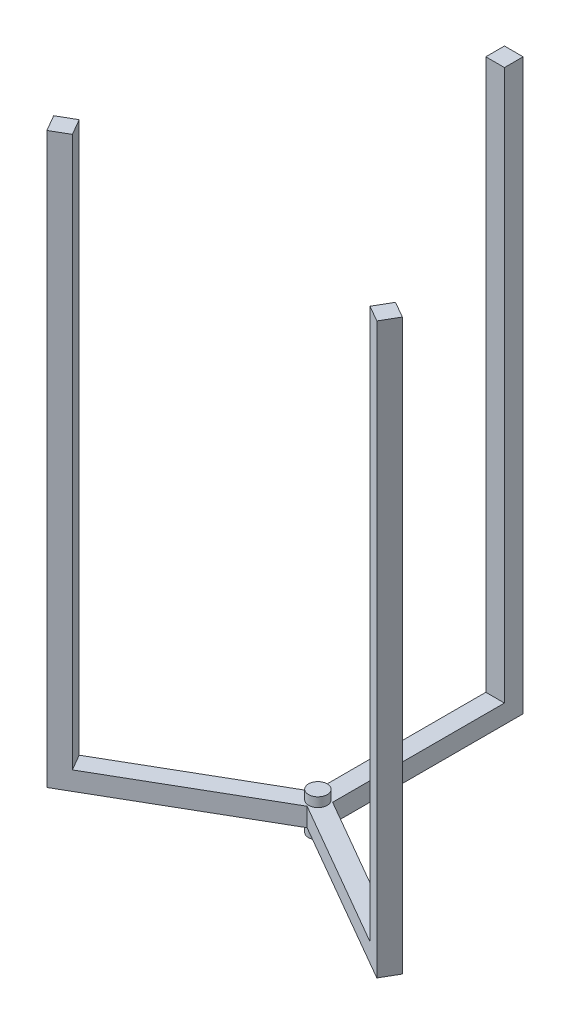
SolidWorks part; units mm, degrees
ref_plane "Plan de face" through (0, 0, 0) normal (0, 0, 1) x (1, 0, 0)
ref_plane "Plan de dessus" through (0, 0, 0) normal (0, 1, 0) x (1, 0, 0)
ref_plane "Plan de droite" through (0, 0, 0) normal (1, 0, 0) x (0, 0, -1)
sketch3d "Esquisse3D1"
  line L0 (0, 0, 0) -> (0, 0, -20)
  line L1 (0, 0, -20) -> (0, 60, -20)
  dimension "D1" = 20
  dimension "D2" = 60
sketch "Esquisse2" plane through (0, 0, 0) normal (0, 0, 1) x (1, 0, 0)
  line L0 (-1, 0) -> (1, 0) construction
  line L1 (-1, 1) -> (1, 1)
  line L2 (-1, 1) -> (-1, -1)
  line L3 (-1, -1) -> (1, -1)
  line L4 (1, 1) -> (1, -1)
  line L5 (0, 1) -> (0, -1) construction
  dimension "D1" = 2
  dimension "D2" = 2
sweep "Balayage2" add profiles "Esquisse2" path "Esquisse3D1"
sketch "Esquisse3" plane through (0, 0, 0) normal (0, 1, 0) x (1, 0, 0)
  circle A0 centre (0, 0) radius 1
  dimension "D1" = 2
extrude "Boss.-Extru.1" add sketch "Esquisse3" along normal mid plane 4
pattern_circular "Répétition circulaire1" count 3 every 120 about axis through (0, 0, 0) along (0, 1, 0) of "Balayage2"
